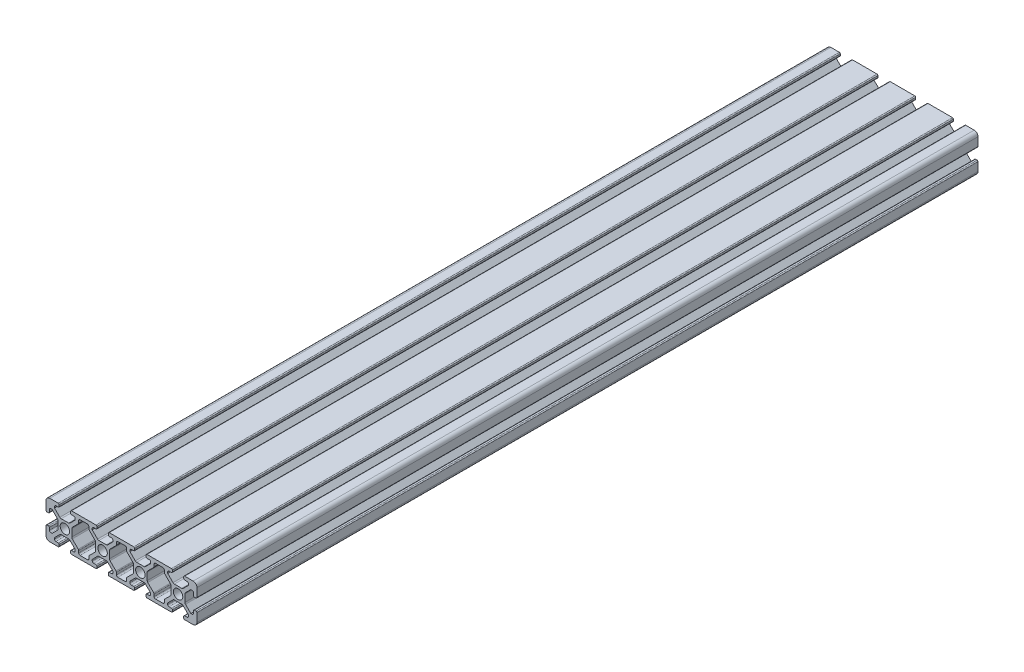
SolidWorks part; units mm, degrees
material "6063-T5"
ref_plane "Front Plane" through (0, 0, 0) normal (0, 0, 1) x (1, 0, 0)
ref_plane "Top Plane" through (0, 0, 0) normal (0, 1, 0) x (1, 0, 0)
ref_plane "Right Plane" through (0, 0, 0) normal (1, 0, 0) x (0, 0, -1)
sketch "Sketch1" plane through (0, 0, 0) normal (0, 0, 1) x (1, 0, 0)
  line L0 (-41.935, 2.3415) -> (-37.435, 2.3415)
  line L1 (36.065, 4.3415) -> (36.065, 8.8415)
  line L2 (34.065, 22.3415) -> (29.565, 22.3415)
  line L3 (-43.935, 20.3415) -> (-43.935, 15.8415)
  line L4 (-10.935, 21.8415) -> (-10.935, 21.0415)
  line L5 (-16.935, 21.8415) -> (-16.935, 21.0415)
  line L6 (-36.935, 21.8415) -> (-36.935, 21.0415)
  line L7 (-30.935, 21.8415) -> (-30.935, 21.0415)
  line L8 (-37.435, 22.3415) -> (-41.935, 22.3415)
  line L9 (9.065, 21.8415) -> (9.065, 21.0415)
  line L10 (3.065, 21.8415) -> (3.065, 21.0415)
  line L11 (29.065, 21.8415) -> (29.065, 21.0415)
  line L12 (23.065, 21.8415) -> (23.065, 21.0415)
  line L13 (-10.935, 3.6415) -> (-10.935, 2.8415)
  line L14 (-16.935, 3.6415) -> (-16.935, 2.8415)
  line L15 (9.065, 3.6415) -> (9.065, 2.8415)
  line L16 (3.065, 3.6415) -> (3.065, 2.8415)
  line L17 (29.065, 3.6415) -> (29.065, 2.8415)
  line L18 (23.065, 3.6415) -> (23.065, 2.8415)
  line L19 (-30.935, 3.6415) -> (-30.935, 2.8415)
  line L20 (-36.935, 3.6415) -> (-36.935, 2.8415)
  line L21 (-30.435, 22.3415) -> (-17.435, 22.3415) construction
  line L22 (-17.435, 22.3415) -> (-30.435, 22.3415)
  line L23 (2.565, 22.3415) -> (-10.435, 22.3415)
  line L24 (22.565, 22.3415) -> (9.565, 22.3415)
  line L25 (29.565, 2.3415) -> (34.065, 2.3415)
  line L26 (9.565, 2.3415) -> (22.565, 2.3415)
  line L27 (-10.435, 2.3415) -> (2.565, 2.3415)
  line L28 (-30.435, 2.3415) -> (-17.435, 2.3415)
  line L29 (35.565, 15.3415) -> (34.765, 15.3415)
  line L30 (35.565, 9.3415) -> (34.765, 9.3415)
  line L31 (-43.435, 15.3415) -> (-42.635, 15.3415)
  line L32 (-43.435, 9.3415) -> (-42.635, 9.3415)
  line L33 (-43.935, 8.8415) -> (-43.935, 4.3415)
  line L34 (36.065, 15.8415) -> (36.065, 20.3415)
  line L35 (-42.135, 15.8415) -> (-42.135, 17.0915)
  line L36 (-38.685, 20.5415) -> (-37.435, 20.5415)
  line L37 (34.265, 17.0915) -> (34.265, 15.8415)
  line L38 (30.815, 4.1415) -> (29.565, 4.1415)
  line L39 (-42.135, 7.5915) -> (-42.135, 8.8415)
  line L40 (-30.435, 20.5415) -> (-29.185, 20.5415)
  line L41 (-37.435, 4.1415) -> (-38.685, 4.1415)
  line L42 (-10.435, 20.5415) -> (-9.185, 20.5415)
  line L43 (-17.435, 4.1415) -> (-18.685, 4.1415)
  line L44 (9.565, 20.5415) -> (10.815, 20.5415)
  line L45 (2.565, 4.1415) -> (1.315, 4.1415)
  line L46 (29.565, 20.5415) -> (30.815, 20.5415)
  line L47 (22.565, 4.1415) -> (21.315, 4.1415)
  line L48 (34.265, 8.8415) -> (34.265, 7.5915)
  line L49 (-31.2649, 16.2843) -> (-28.435, 19.1142)
  line L50 (-31.2649, 8.3986) -> (-28.435, 5.5687)
  line L51 (-11.2649, 16.2843) -> (-8.435, 19.1142)
  line L52 (-9.9921, 15.0116) -> (-6.8546, 18.149)
  line L53 (-16.6051, 16.2843) -> (-19.435, 19.1142)
  line L54 (-21.0153, 18.149) -> (-17.8778, 15.0116)
  line L55 (-16.6051, 8.3986) -> (-19.435, 5.5687)
  line L56 (-21.0153, 6.5339) -> (-17.8778, 9.6714)
  line L57 (3.3949, 16.2843) -> (0.565, 19.1142)
  line L58 (-1.0153, 18.149) -> (2.1222, 15.0116)
  line L59 (3.3949, 8.3986) -> (0.565, 5.5687)
  line L60 (-1.0153, 6.5339) -> (2.1222, 9.6714)
  line L61 (23.3949, 16.2843) -> (20.565, 19.1142)
  line L62 (18.9847, 18.149) -> (22.1222, 15.0116)
  line L63 (23.3949, 8.3986) -> (20.565, 5.5687)
  line L64 (18.9847, 6.5339) -> (22.1222, 9.6714)
  line L65 (-9.9921, 9.6714) -> (-6.8546, 6.5339)
  line L66 (-29.9921, 15.0116) -> (-26.8546, 18.149)
  line L67 (-37.8778, 9.6714) -> (-40.7077, 6.8415)
  line L68 (-36.6051, 8.3986) -> (-39.435, 5.5687)
  line L69 (-36.6051, 16.2843) -> (-39.435, 19.1142)
  line L70 (-11.2649, 8.3986) -> (-8.435, 5.5687)
  line L71 (-29.9921, 9.6714) -> (-26.8546, 6.5339)
  line L72 (8.7351, 16.2843) -> (11.565, 19.1142)
  line L73 (-37.8778, 15.0116) -> (-40.7077, 17.8415)
  line L74 (10.0079, 15.0116) -> (13.1454, 18.149)
  line L75 (10.0079, 9.6714) -> (13.1454, 6.5339)
  line L76 (8.7351, 8.3986) -> (11.565, 5.5687)
  line L77 (28.7351, 16.2843) -> (31.565, 19.1142)
  line L78 (30.0079, 15.0116) -> (32.8378, 17.8415)
  line L79 (30.0079, 9.6714) -> (32.8378, 6.8415)
  line L80 (28.7351, 8.3986) -> (31.565, 5.5687)
  line L81 (-15.898, 15.9915) -> (-11.972, 15.9915)
  line L82 (-25.885, 20.5415) -> (-21.985, 20.5415)
  line L83 (-29.185, 4.1415) -> (-30.435, 4.1415)
  line L84 (-28.435, 19.7915) -> (-28.435, 19.1142)
  line L85 (-9.185, 4.1415) -> (-10.435, 4.1415)
  line L86 (-39.435, 19.7915) -> (-39.435, 19.1142)
  line L87 (10.815, 4.1415) -> (9.565, 4.1415)
  line L88 (-19.435, 19.7915) -> (-19.435, 19.1142)
  line L89 (-18.685, 20.5415) -> (-17.435, 20.5415)
  line L90 (1.315, 20.5415) -> (2.565, 20.5415)
  line L91 (-10.285, 14.3044) -> (-10.285, 10.3785)
  line L92 (-11.972, 8.6915) -> (-15.898, 8.6915)
  line L93 (-17.585, 10.3785) -> (-17.585, 14.3044)
  line L94 (21.315, 20.5415) -> (22.565, 20.5415)
  line L95 (0.565, 19.7915) -> (0.565, 19.1142)
  line L96 (-8.435, 19.7915) -> (-8.435, 19.1142)
  line L97 (-30.285, 14.3044) -> (-30.285, 10.3785)
  line L98 (-31.972, 8.6915) -> (-35.898, 8.6915)
  line L99 (-37.585, 10.3785) -> (-37.585, 14.3044)
  line L100 (-35.898, 15.9915) -> (-31.972, 15.9915)
  line L101 (4.102, 15.9915) -> (8.028, 15.9915)
  line L102 (9.715, 14.3044) -> (9.715, 10.3785)
  line L103 (8.028, 8.6915) -> (4.102, 8.6915)
  line L104 (2.415, 10.3785) -> (2.415, 14.3044)
  line L105 (24.102, 15.9915) -> (28.028, 15.9915)
  line L106 (29.715, 14.3044) -> (29.715, 10.3785)
  line L107 (28.028, 8.6915) -> (24.102, 8.6915)
  line L108 (22.415, 10.3785) -> (22.415, 14.3044)
  line L109 (20.565, 19.7915) -> (20.565, 19.1142)
  line L110 (11.565, 19.7915) -> (11.565, 19.1142)
  line L111 (-39.435, 4.8915) -> (-39.435, 5.5687)
  line L112 (31.565, 19.7915) -> (31.565, 19.1142)
  line L113 (-19.435, 4.8915) -> (-19.435, 5.5687)
  line L114 (-28.435, 4.8915) -> (-28.435, 5.5687)
  line L115 (0.565, 4.8915) -> (0.565, 5.5687)
  line L116 (-8.435, 4.8915) -> (-8.435, 5.5687)
  line L117 (20.565, 4.8915) -> (20.565, 5.5687)
  line L118 (11.565, 4.8915) -> (11.565, 5.5687)
  line L119 (-41.385, 17.8415) -> (-40.7077, 17.8415)
  line L120 (31.565, 4.8915) -> (31.565, 5.5687)
  line L121 (-41.385, 6.8415) -> (-40.7077, 6.8415)
  line L122 (33.515, 17.8415) -> (32.8378, 17.8415)
  line L123 (-26.635, 19.7915) -> (-26.635, 18.6793)
  line L124 (33.515, 6.8415) -> (32.8378, 6.8415)
  line L125 (-21.235, 19.7915) -> (-21.235, 18.6793)
  line L126 (-5.885, 20.5415) -> (-1.985, 20.5415)
  line L127 (-6.635, 19.7915) -> (-6.635, 18.6793)
  line L128 (-1.235, 19.7915) -> (-1.235, 18.6793)
  line L129 (14.115, 20.5415) -> (18.015, 20.5415)
  line L130 (13.365, 19.7915) -> (13.365, 18.6793)
  line L131 (18.765, 19.7915) -> (18.765, 18.6793)
  line L132 (-26.635, 6.0036) -> (-26.635, 4.8915)
  line L133 (-25.885, 4.1415) -> (-21.985, 4.1415)
  line L134 (-21.235, 4.8915) -> (-21.235, 6.0036)
  line L135 (-6.635, 6.0036) -> (-6.635, 4.8915)
  line L136 (-5.885, 4.1415) -> (-1.985, 4.1415)
  line L137 (-1.235, 4.8915) -> (-1.235, 6.0036)
  line L138 (13.365, 6.0036) -> (13.365, 4.8915)
  line L139 (14.115, 4.1415) -> (18.015, 4.1415)
  line L140 (18.765, 4.8915) -> (18.765, 6.0036)
  circle A0 centre (-33.935, 12.3415) radius 2.5
  circle A1 centre (-13.935, 12.3415) radius 2.5
  circle A2 centre (6.065, 12.3415) radius 2.5
  circle A3 centre (26.065, 12.3415) radius 2.5
  arc A4 (34.065, 2.3415) -> (36.065, 4.3415) centre (34.065, 4.3415) ccw
  arc A5 (36.065, 20.3415) -> (34.065, 22.3415) centre (34.065, 20.3415) ccw
  arc A6 (-41.935, 2.3415) -> (-43.935, 4.3415) centre (-41.935, 4.3415) cw
  arc A7 (-41.935, 22.3415) -> (-43.935, 20.3415) centre (-41.935, 20.3415) ccw
  arc A8 (-31.2649, 16.2843) -> (-31.972, 15.9915) centre (-31.972, 16.9915) cw
  arc A9 (-36.6051, 16.2843) -> (-35.898, 15.9915) centre (-35.898, 16.9915) ccw
  arc A10 (-37.8778, 15.0116) -> (-37.585, 14.3044) centre (-38.585, 14.3044) cw
  arc A11 (-37.8778, 9.6714) -> (-37.585, 10.3785) centre (-38.585, 10.3785) ccw
  arc A12 (-36.6051, 8.3986) -> (-35.898, 8.6915) centre (-35.898, 7.6915) cw
  arc A13 (-31.2649, 8.3986) -> (-31.972, 8.6915) centre (-31.972, 7.6915) ccw
  arc A14 (-11.2649, 8.3986) -> (-11.972, 8.6915) centre (-11.972, 7.6915) ccw
  arc A15 (-16.6051, 8.3986) -> (-15.898, 8.6915) centre (-15.898, 7.6915) cw
  arc A16 (-16.6051, 16.2843) -> (-15.898, 15.9915) centre (-15.898, 16.9915) ccw
  arc A17 (-11.2649, 16.2843) -> (-11.972, 15.9915) centre (-11.972, 16.9915) cw
  arc A18 (3.3949, 8.3986) -> (4.102, 8.6915) centre (4.102, 7.6915) cw
  arc A19 (8.7351, 8.3986) -> (8.028, 8.6915) centre (8.028, 7.6915) ccw
  arc A20 (8.7351, 16.2843) -> (8.028, 15.9915) centre (8.028, 16.9915) cw
  arc A21 (3.3949, 16.2843) -> (4.102, 15.9915) centre (4.102, 16.9915) ccw
  arc A22 (28.7351, 16.2843) -> (28.028, 15.9915) centre (28.028, 16.9915) cw
  arc A23 (23.3949, 16.2843) -> (24.102, 15.9915) centre (24.102, 16.9915) ccw
  arc A24 (23.3949, 8.3986) -> (24.102, 8.6915) centre (24.102, 7.6915) cw
  arc A25 (28.7351, 8.3986) -> (28.028, 8.6915) centre (28.028, 7.6915) ccw
  arc A26 (30.0079, 9.6714) -> (29.715, 10.3785) centre (30.715, 10.3785) cw
  arc A27 (30.0079, 15.0116) -> (29.715, 14.3044) centre (30.715, 14.3044) ccw
  arc A28 (22.1222, 9.6714) -> (22.415, 10.3785) centre (21.415, 10.3785) ccw
  arc A29 (22.1222, 15.0116) -> (22.415, 14.3044) centre (21.415, 14.3044) cw
  arc A30 (10.0079, 9.6714) -> (9.715, 10.3785) centre (10.715, 10.3785) cw
  arc A31 (10.0079, 15.0116) -> (9.715, 14.3044) centre (10.715, 14.3044) ccw
  arc A32 (34.265, 17.0915) -> (33.515, 17.8415) centre (33.515, 17.0915) ccw
  arc A33 (31.565, 19.7915) -> (30.815, 20.5415) centre (30.815, 19.7915) ccw
  arc A34 (34.265, 7.5915) -> (33.515, 6.8415) centre (33.515, 7.5915) cw
  arc A35 (31.565, 4.8915) -> (30.815, 4.1415) centre (30.815, 4.8915) cw
  arc A36 (2.1222, 9.6714) -> (2.415, 10.3785) centre (1.415, 10.3785) ccw
  arc A37 (2.1222, 15.0116) -> (2.415, 14.3044) centre (1.415, 14.3044) cw
  arc A38 (-9.9921, 9.6714) -> (-10.285, 10.3785) centre (-9.285, 10.3785) cw
  arc A39 (-9.9921, 15.0116) -> (-10.285, 14.3044) centre (-9.285, 14.3044) ccw
  arc A40 (-29.9921, 15.0116) -> (-30.285, 14.3044) centre (-29.285, 14.3044) ccw
  arc A41 (-29.9921, 9.6714) -> (-30.285, 10.3785) centre (-29.285, 10.3785) cw
  arc A42 (-17.8778, 9.6714) -> (-17.585, 10.3785) centre (-18.585, 10.3785) ccw
  arc A43 (-17.8778, 15.0116) -> (-17.585, 14.3044) centre (-18.585, 14.3044) cw
  arc A44 (21.315, 4.1415) -> (20.565, 4.8915) centre (21.315, 4.8915) cw
  arc A45 (18.015, 4.1415) -> (18.765, 4.8915) centre (18.015, 4.8915) ccw
  arc A46 (13.365, 4.8915) -> (14.115, 4.1415) centre (14.115, 4.8915) ccw
  arc A47 (10.815, 4.1415) -> (11.565, 4.8915) centre (10.815, 4.8915) ccw
  arc A48 (1.315, 4.1415) -> (0.565, 4.8915) centre (1.315, 4.8915) cw
  arc A49 (20.565, 19.7915) -> (21.315, 20.5415) centre (21.315, 19.7915) cw
  arc A50 (18.015, 20.5415) -> (18.765, 19.7915) centre (18.015, 19.7915) cw
  arc A51 (14.115, 20.5415) -> (13.365, 19.7915) centre (14.115, 19.7915) ccw
  arc A52 (9.065, 21.0415) -> (9.565, 20.5415) centre (9.565, 21.0415) ccw
  arc A53 (9.065, 21.8415) -> (9.565, 22.3415) centre (9.565, 21.8415) cw
  arc A54 (23.065, 21.0415) -> (22.565, 20.5415) centre (22.565, 21.0415) cw
  arc A55 (23.065, 21.8415) -> (22.565, 22.3415) centre (22.565, 21.8415) ccw
  arc A56 (29.065, 21.0415) -> (29.565, 20.5415) centre (29.565, 21.0415) ccw
  arc A57 (29.065, 21.8415) -> (29.565, 22.3415) centre (29.565, 21.8415) cw
  arc A58 (34.765, 15.3415) -> (34.265, 15.8415) centre (34.765, 15.8415) cw
  arc A59 (35.565, 15.3415) -> (36.065, 15.8415) centre (35.565, 15.8415) ccw
  arc A60 (34.765, 9.3415) -> (34.265, 8.8415) centre (34.765, 8.8415) ccw
  arc A61 (35.565, 9.3415) -> (36.065, 8.8415) centre (35.565, 8.8415) cw
  arc A62 (29.065, 2.8415) -> (29.565, 2.3415) centre (29.565, 2.8415) ccw
  arc A63 (29.065, 3.6415) -> (29.565, 4.1415) centre (29.565, 3.6415) cw
  arc A64 (23.065, 2.8415) -> (22.565, 2.3415) centre (22.565, 2.8415) cw
  arc A65 (23.065, 3.6415) -> (22.565, 4.1415) centre (22.565, 3.6415) ccw
  arc A66 (9.065, 2.8415) -> (9.565, 2.3415) centre (9.565, 2.8415) ccw
  arc A67 (9.065, 3.6415) -> (9.565, 4.1415) centre (9.565, 3.6415) cw
  arc A68 (3.065, 2.8415) -> (2.565, 2.3415) centre (2.565, 2.8415) cw
  arc A69 (3.065, 3.6415) -> (2.565, 4.1415) centre (2.565, 3.6415) ccw
  arc A70 (-10.935, 2.8415) -> (-10.435, 2.3415) centre (-10.435, 2.8415) ccw
  arc A71 (-10.935, 3.6415) -> (-10.435, 4.1415) centre (-10.435, 3.6415) cw
  arc A72 (-16.935, 2.8415) -> (-17.435, 2.3415) centre (-17.435, 2.8415) cw
  arc A73 (-16.935, 3.6415) -> (-17.435, 4.1415) centre (-17.435, 3.6415) ccw
  arc A74 (3.065, 21.0415) -> (2.565, 20.5415) centre (2.565, 21.0415) cw
  arc A75 (3.065, 21.8415) -> (2.565, 22.3415) centre (2.565, 21.8415) ccw
  arc A76 (-10.935, 21.0415) -> (-10.435, 20.5415) centre (-10.435, 21.0415) ccw
  arc A77 (-10.935, 21.8415) -> (-10.435, 22.3415) centre (-10.435, 21.8415) cw
  arc A78 (-16.935, 21.0415) -> (-17.435, 20.5415) centre (-17.435, 21.0415) cw
  arc A79 (-16.935, 21.8415) -> (-17.435, 22.3415) centre (-17.435, 21.8415) ccw
  arc A80 (-30.935, 21.0415) -> (-30.435, 20.5415) centre (-30.435, 21.0415) ccw
  arc A81 (-30.435, 22.3415) -> (-30.935, 21.8415) centre (-30.435, 21.8415) ccw
  arc A82 (-30.935, 2.8415) -> (-30.435, 2.3415) centre (-30.435, 2.8415) ccw
  arc A83 (-30.935, 3.6415) -> (-30.435, 4.1415) centre (-30.435, 3.6415) cw
  arc A84 (-36.935, 2.8415) -> (-37.435, 2.3415) centre (-37.435, 2.8415) cw
  arc A85 (-36.935, 3.6415) -> (-37.435, 4.1415) centre (-37.435, 3.6415) ccw
  arc A86 (-43.935, 8.8415) -> (-43.435, 9.3415) centre (-43.435, 8.8415) cw
  arc A87 (-42.635, 9.3415) -> (-42.135, 8.8415) centre (-42.635, 8.8415) cw
  arc A88 (-43.935, 15.8415) -> (-43.435, 15.3415) centre (-43.435, 15.8415) ccw
  arc A89 (-42.635, 15.3415) -> (-42.135, 15.8415) centre (-42.635, 15.8415) ccw
  arc A90 (-37.435, 22.3415) -> (-36.935, 21.8415) centre (-37.435, 21.8415) cw
  arc A91 (-36.935, 21.0415) -> (-37.435, 20.5415) centre (-37.435, 21.0415) cw
  arc A92 (11.565, 19.7915) -> (10.815, 20.5415) centre (10.815, 19.7915) ccw
  arc A93 (0.565, 19.7915) -> (1.315, 20.5415) centre (1.315, 19.7915) cw
  arc A94 (-6.635, 4.8915) -> (-5.885, 4.1415) centre (-5.885, 4.8915) ccw
  arc A95 (-5.885, 20.5415) -> (-6.635, 19.7915) centre (-5.885, 19.7915) ccw
  arc A96 (-1.985, 20.5415) -> (-1.235, 19.7915) centre (-1.985, 19.7915) cw
  arc A97 (-1.985, 4.1415) -> (-1.235, 4.8915) centre (-1.985, 4.8915) ccw
  arc A98 (-9.185, 4.1415) -> (-8.435, 4.8915) centre (-9.185, 4.8915) ccw
  arc A99 (-18.685, 4.1415) -> (-19.435, 4.8915) centre (-18.685, 4.8915) cw
  arc A100 (-29.185, 4.1415) -> (-28.435, 4.8915) centre (-29.185, 4.8915) ccw
  arc A101 (-38.685, 4.1415) -> (-39.435, 4.8915) centre (-38.685, 4.8915) cw
  arc A102 (-41.385, 6.8415) -> (-42.135, 7.5915) centre (-41.385, 7.5915) cw
  arc A103 (-42.135, 17.0915) -> (-41.385, 17.8415) centre (-41.385, 17.0915) cw
  arc A104 (-19.435, 19.7915) -> (-18.685, 20.5415) centre (-18.685, 19.7915) cw
  arc A105 (-9.185, 20.5415) -> (-8.435, 19.7915) centre (-9.185, 19.7915) cw
  arc A106 (-21.985, 20.5415) -> (-21.235, 19.7915) centre (-21.985, 19.7915) cw
  arc A107 (-25.885, 20.5415) -> (-26.635, 19.7915) centre (-25.885, 19.7915) ccw
  arc A108 (-28.435, 19.7915) -> (-29.185, 20.5415) centre (-29.185, 19.7915) ccw
  arc A109 (-38.685, 20.5415) -> (-39.435, 19.7915) centre (-38.685, 19.7915) ccw
  arc A110 (18.765, 6.0036) -> (18.9847, 6.5339) centre (19.515, 6.0036) cw
  arc A111 (13.365, 6.0036) -> (13.1454, 6.5339) centre (12.615, 6.0036) ccw
  arc A112 (18.765, 18.6793) -> (18.9847, 18.149) centre (19.515, 18.6793) ccw
  arc A113 (13.365, 18.6793) -> (13.1454, 18.149) centre (12.615, 18.6793) cw
  arc A114 (-1.235, 6.0036) -> (-1.0153, 6.5339) centre (-0.485, 6.0036) cw
  arc A115 (-6.635, 6.0036) -> (-6.8546, 6.5339) centre (-7.385, 6.0036) ccw
  arc A116 (-1.235, 18.6793) -> (-1.0153, 18.149) centre (-0.485, 18.6793) ccw
  arc A117 (-6.635, 18.6793) -> (-6.8546, 18.149) centre (-7.385, 18.6793) cw
  arc A118 (-21.235, 18.6793) -> (-21.0153, 18.149) centre (-20.485, 18.6793) ccw
  arc A119 (-26.635, 18.6793) -> (-26.8546, 18.149) centre (-27.385, 18.6793) cw
  arc A120 (-26.635, 6.0036) -> (-26.8546, 6.5339) centre (-27.385, 6.0036) ccw
  arc A121 (-21.235, 6.0036) -> (-21.0153, 6.5339) centre (-20.485, 6.0036) cw
  arc A122 (-21.985, 4.1415) -> (-21.235, 4.8915) centre (-21.985, 4.8915) ccw
  arc A123 (-26.635, 4.8915) -> (-25.885, 4.1415) centre (-25.885, 4.8915) ccw
extrude "Boss-Extrude1" add sketch "Sketch1" along normal blind 414
